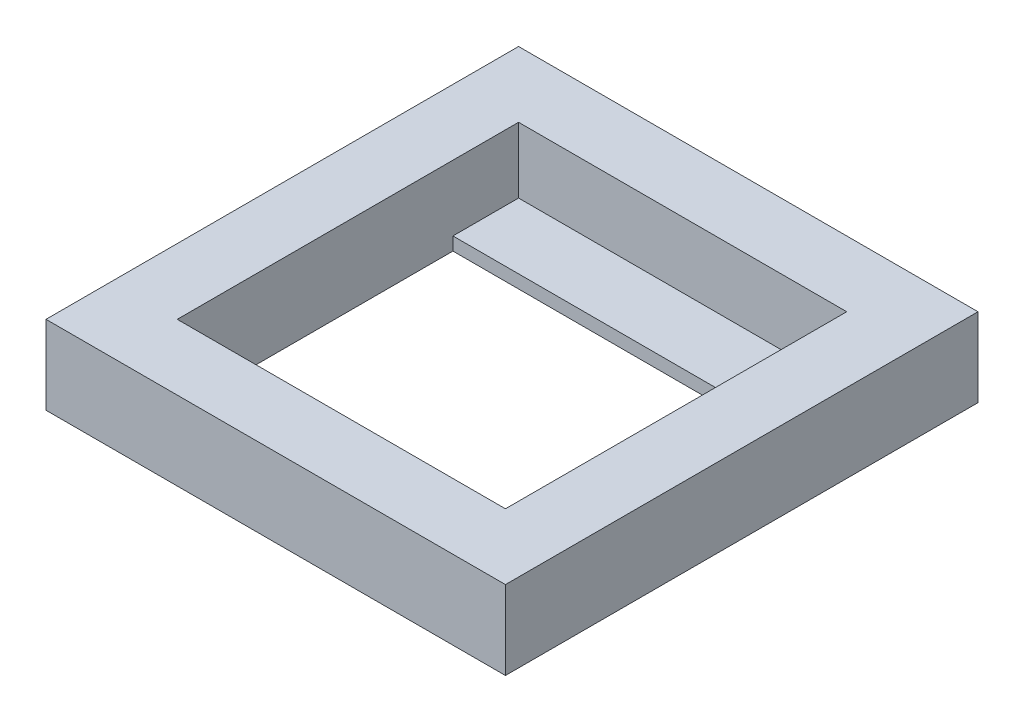
SolidWorks part; units mm, degrees
ref_plane "Front Plane" through (0, 0, 0) normal (0, 0, 1) x (1, 0, 0)
ref_plane "Top Plane" through (0, 0, 0) normal (0, 1, 0) x (1, 0, 0)
ref_plane "Right Plane" through (0, 0, 0) normal (1, 0, 0) x (0, 0, -1)
sketch "Sketch1" plane through (0, 0, 0) normal (0, 1, 0) x (1, 0, 0)
  line L1 (0, 0) -> (70, 0)
  line L2 (0, 0) -> (0, 72)
  line L3 (0, 72) -> (70, 72)
  line L4 (70, 0) -> (70, 72)
  dimension "D1" = 72
  dimension "D2" = 70
extrude "Boss-Extrude1" add sketch "Sketch1" along normal blind 2
sketch "Sketch2" plane through (0, 2, 0) normal (0, 1, 0) x (1, 0, 0)
  line L0 (0, 0) -> (70, 0) construction
  line L1 (10, 52) -> (60, 52)
  line L2 (10, 52) -> (10, 20)
  line L3 (10, 20) -> (60, 20)
  line L4 (60, 52) -> (60, 20)
  line L5 (70, 72) -> (0, 72) construction
  line L6 (0, 72) -> (0, 0) construction
  line L7 (70, 0) -> (70, 72) construction
  dimension "D1" = 20
  dimension "D2" = 20
  dimension "D3" = 10
  dimension "D4" = 10
extrude "Cut-Extrude1" cut sketch "Sketch2" against normal blind 12
sketch "Sketch3" plane through (0, 2, 0) normal (0, 1, 0) x (1, 0, 0)
  line L0 (70, 0) -> (70, 72) construction
  line L1 (0, 72) -> (70, 72)
  line L2 (0, 72) -> (0, 62)
  line L3 (0, 62) -> (70, 62)
  line L4 (70, 72) -> (70, 62)
  line L5 (0, 0) -> (70, 0) construction
  line L6 (70, 72) -> (60, 72)
  line L7 (70, 72) -> (70, 0)
  line L8 (70, 0) -> (60, 0)
  line L9 (60, 72) -> (60, 0)
  line L11 (70, 10) -> (0, 10)
  line L12 (70, 10) -> (70, 0)
  line L13 (70, 0) -> (0, 0)
  line L14 (0, 10) -> (0, 0)
  line L15 (0, 0) -> (10, 0)
  line L16 (0, 0) -> (0, 72)
  line L17 (0, 72) -> (10, 72)
  line L18 (10, 0) -> (10, 72)
  line M13 (0, 72) -> (0, 0)
  line M14 (0, 0) -> (70, 0)
  line M15 (70, 0) -> (70, 72)
  line M16 (70, 72) -> (0, 72)
  dimension "D1" = 10
  dimension "D2" = 10
  dimension "D3" = 10
  dimension "D4" = 10
extrude "Boss-Extrude2" add sketch "Sketch3" along normal blind 10 contours L11 L18 L3 M13 | L3 L18 M16 M13 | L18 L3 L9 L1 | L18 L11 M14 M13 | L18 L13 L9 L11 | L11 L9 M15 M14 | L11 L7 L3 L9 | L9 L3 M16 M15
